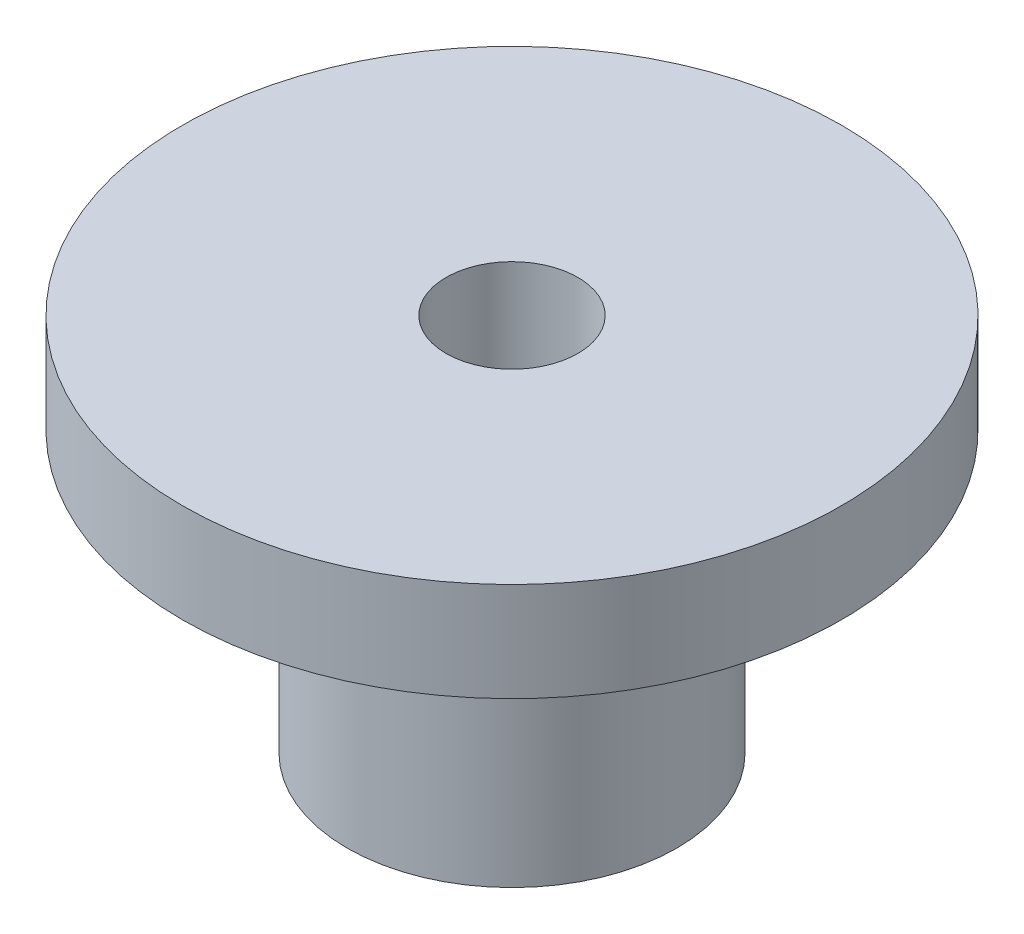
SolidWorks part; units mm, degrees
ref_plane "前视基准面" through (0, 0, 0) normal (0, 0, 1) x (1, 0, 0)
ref_plane "上视基准面" through (0, 0, 0) normal (0, 1, 0) x (1, 0, 0)
ref_plane "右视基准面" through (0, 0, 0) normal (1, 0, 0) x (0, 0, -1)
other "Configuration Table"
sketch "草图1" plane through (0, 0, 0) normal (0, 1, 0) x (1, 0, 0)
  circle A0 centre (0, 0) radius 5
  circle A1 centre (0, 0) radius 2
  dimension "D1" = 10
  dimension "D2" = 4
extrude "凸台-拉伸1" add sketch "草图1" along normal blind 8.5
sketch "草图2" plane through (0, 8.5, 0) normal (0, 1, 0) x (1, 0, 0)
  circle A0 centre (0, 0) radius 10
  circle A1 centre (0, 0) radius 2 construction
  circle A2 centre (0, 0) radius 2
  dimension "D1" = 20
extrude "凸台-拉伸2" add sketch "草图2" along normal blind 3
